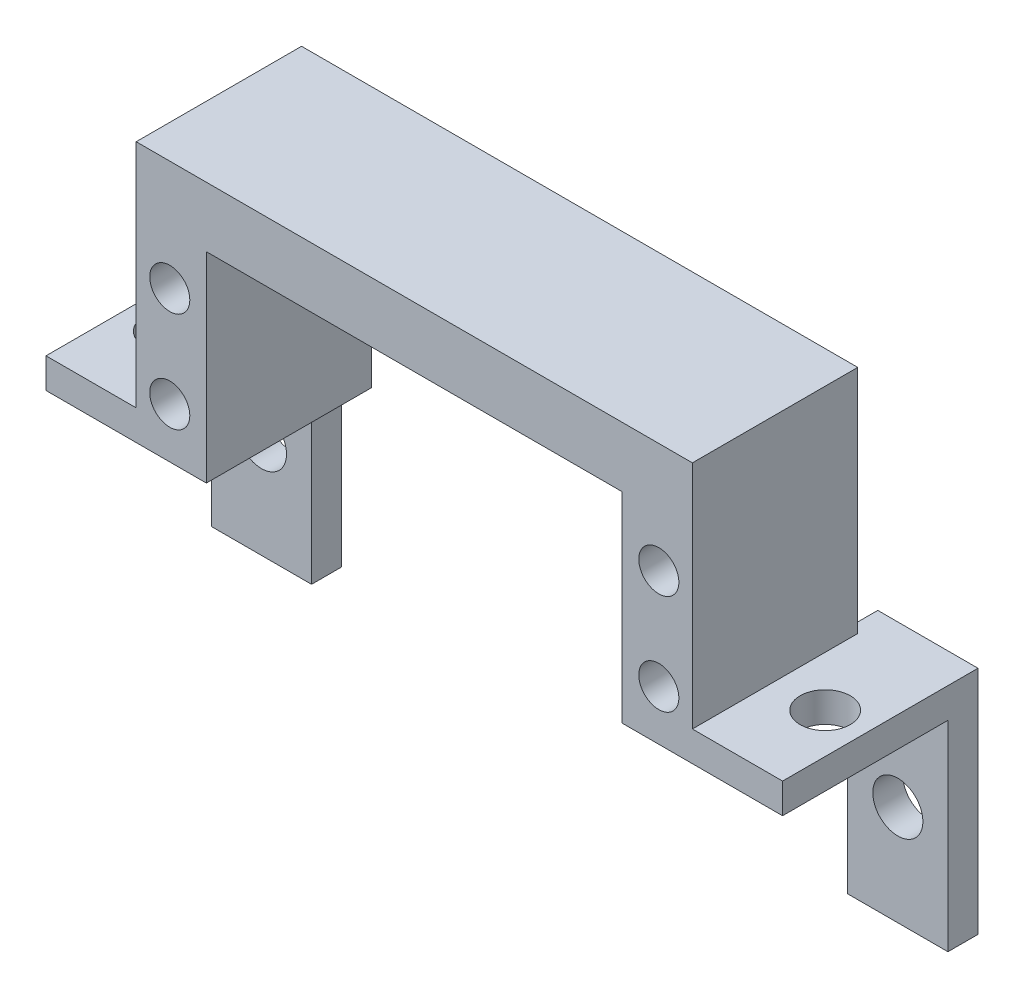
SolidWorks part; units mm, degrees
ref_plane "前视基准面" through (0, 0, 0) normal (0, 0, 1) x (1, 0, 0)
ref_plane "上视基准面" through (0, 0, 0) normal (0, 1, 0) x (1, 0, 0)
ref_plane "右视基准面" through (0, 0, 0) normal (1, 0, 0) x (0, 0, -1)
sketch "草图1" plane through (0, 0, 0) normal (0, 0, 1) x (1, 0, 0)
  line L0 (0, 38.2514) -> (0, 0) construction
  line L1 (0, 0) -> (26.75, 0)
  line L2 (26.75, 0) -> (26.75, -20)
  line L3 (26.75, -20) -> (36.75, -20)
  line L4 (0, -6) -> (20.75, -6)
  line L5 (20.75, -6) -> (20.75, -26)
  line L6 (20.75, -26) -> (36.75, -26)
  line L7 (-36.75, -20) -> (-36.75, -26)
  line L8 (36.75, -20) -> (36.75, -26)
  line L9 (-20.75, -26) -> (-36.75, -26)
  line L10 (-20.75, -6) -> (-20.75, -26)
  line L11 (0, -6) -> (-20.75, -6)
  line L12 (-26.75, -20) -> (-36.75, -20)
  line L13 (-26.75, 0) -> (-26.75, -20)
  line L14 (0, 0) -> (-26.75, 0)
  point P3 (26.75, -20)
  point P11 (26.75, -20)
  point P19 (26.75, -20)
  point P20 (26.75, -20)
  point P21 (26.75, -20)
  point P22 (0, 0)
  point P23 (26.75, -20)
  dimension "D2" = 41.5
  dimension "D3" = 20
  dimension "D4" = 10
  dimension "D5" = 0
  dimension "D1" = 6
extrude "凸台-拉伸1" add sketch "草图1" along normal blind 16.5
sketch "草图2" plane through (0, -20, 0) normal (0, 1, 0) x (1, 0, 0)
  line L0 (36.75, -16.5) -> (26.75, -16.5) construction
  line L1 (36.75, -16.5) -> (36.75, 0) construction
  line L2 (-36.75, -16.5) -> (-36.75, 0) construction
  line L3 (-26.75, -16.5) -> (-36.75, -16.5) construction
  circle A0 centre (32.75, -8.25) radius 2.5
  circle A1 centre (-32.75, -8.25) radius 2.5
  point P8 (0, 0)
  dimension "D1" = 5
  dimension "D2" = 8.25
  dimension "D3" = 4
  dimension "D4" = 5
  dimension "D5" = 4
  dimension "D6" = 8.25
extrude "切除-拉伸1" cut sketch "草图2" against normal blind 16.5
sketch "草图3" plane through (0, -20, 0) normal (0, 1, 0) x (1, 0, 0)
  line L1 (36.75, 0) -> (26.75, 0)
  line L2 (36.75, 0) -> (36.75, -16.5)
  line L3 (36.75, -16.5) -> (26.75, -16.5)
  line L4 (26.75, 0) -> (26.75, -16.5)
  line L5 (-36.75, 0) -> (-26.75, 0)
  line L6 (-36.75, 0) -> (-36.75, -16.5)
  line L7 (-36.75, -16.5) -> (-26.75, -16.5)
  line L8 (-26.75, 0) -> (-26.75, -16.5)
extrude "切除-拉伸2" cut sketch "草图3" against normal blind 3
sketch "草图5" plane through (0, 0, 0) normal (0, 0, -1) x (-1, 0, 0)
  line L0 (20.75, -16) -> (-20.75, -16) construction
  line L1 (20.75, -26) -> (20.75, -6) construction
  line L2 (-20.75, -6) -> (-20.75, -26) construction
  line L3 (0, 0) -> (0, -37.9358) construction
  line L4 (-26.75, 0) -> (26.75, 0) construction
  circle A0 centre (-24.4, -11) radius 2
  circle A1 centre (-24.4, -21) radius 2
  circle A2 centre (24.4, -21) radius 2
  circle A3 centre (24.4, -11) radius 2
  dimension "D1" = 4
  dimension "D2" = 4
  dimension "D3" = 10
  dimension "D4" = 5
  dimension "D5" = 24.4
  dimension "D6" = 24.4
extrude "切除-拉伸4" cut sketch "草图5" against normal through all
sketch "草图6" plane through (0, 0, 0) normal (0, 0, -1) x (-1, 0, 0)
  line L1 (-26.75, -23) -> (-36.75, -23)
  line L2 (-26.75, -23) -> (-26.75, -46)
  line L3 (-26.75, -46) -> (-36.75, -46)
  line L4 (-36.75, -23) -> (-36.75, -46)
  line L5 (26.75, -23) -> (36.75, -23)
  line L6 (26.75, -23) -> (26.75, -46)
  line L7 (26.75, -46) -> (36.75, -46)
  line L8 (36.75, -23) -> (36.75, -46)
  dimension "D1" = 23
extrude "凸台-拉伸2" add sketch "草图6" along normal blind 3
sketch "草图7" plane through (0, 0, -3) normal (0, 0, -1) x (-1, 0, 0)
  line L0 (-36.75, -46) -> (-26.75, -46) construction
  line L1 (-36.75, -23) -> (-36.75, -46) construction
  line L2 (26.75, -46) -> (36.75, -46) construction
  line L3 (26.75, -23) -> (26.75, -46) construction
  circle A0 centre (-31.75, -36) radius 2.5
  circle A1 centre (31.75, -36) radius 2.5
  dimension "D1" = 5
  dimension "D2" = 10
  dimension "D3" = 5
  dimension "D4" = 5
  dimension "D5" = 10
  dimension "D6" = 5
extrude "切除-拉伸5" cut sketch "草图7" against normal blind 3
sketch "Sketch2" plane through (-26.75, 0, 0) normal (-1, 0, 0) x (0, 0, 1)
  line L1 (0, 0) -> (16.5, 0)
  line L2 (0, 0) -> (0, -23)
  line L3 (0, -23) -> (16.5, -23)
  line L4 (16.5, 0) -> (16.5, -23)
extrude "Boss-Extrude1" add sketch "Sketch2" along normal blind 1
sketch "Sketch3" plane through (26.75, 0, 0) normal (1, 0, 0) x (0, 0, -1)
  line L0 (0, -23) -> (0, 0) construction
  line L1 (-16.5, 0) -> (0, 0)
  line L2 (-16.5, 0) -> (-16.5, -23)
  line L3 (-16.5, -23) -> (0, -23)
  line L4 (0, 0) -> (0, -23)
extrude "Boss-Extrude2" add sketch "Sketch3" along normal blind 1
